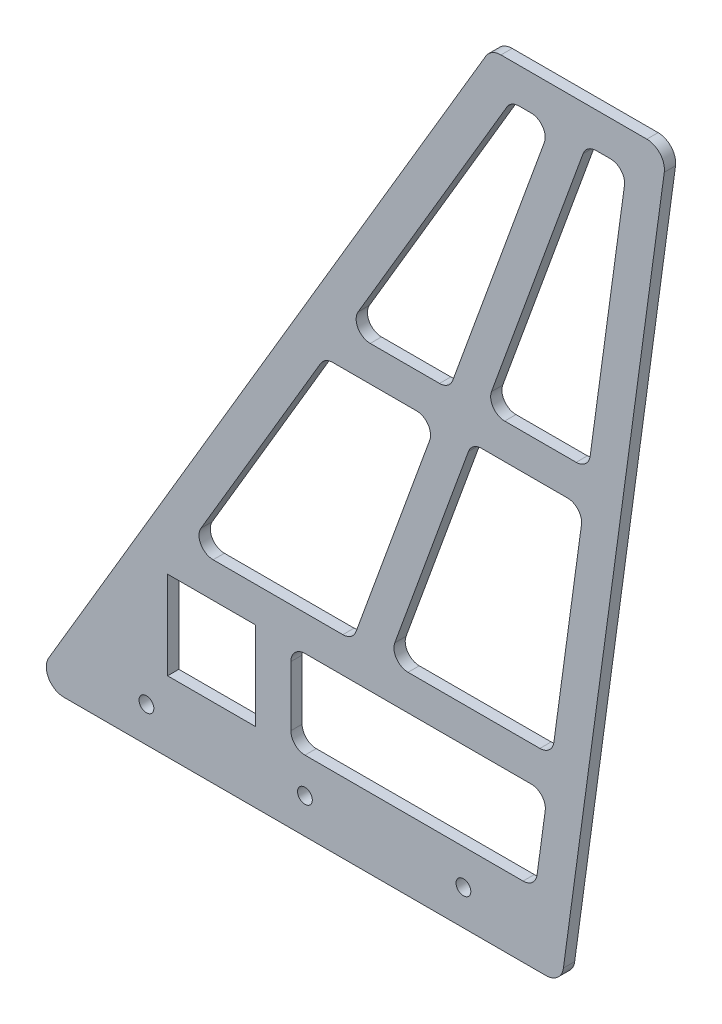
SolidWorks part; units mm, degrees
ref_plane "Спереди" through (0, 0, 0) normal (0, 0, 1) x (1, 0, 0)
ref_plane "Сверху" through (0, 0, 0) normal (0, 1, 0) x (1, 0, 0)
ref_plane "Справа" through (0, 0, 0) normal (1, 0, 0) x (0, 0, -1)
other "Configuration Table"
sketch "Эскиз1" plane through (0, 0, 0) normal (0, 0, 1) x (1, 0, 0)
  line L0 (0, 0) -> (150, 0)
  line L1 (150, 0) -> (180, 220)
  line L2 (180, 220) -> (130, 220)
  line L3 (130, 220) -> (0, 0)
  line L4 (130, 220) -> (130, 20) construction
  line L5 (135.7063, 210) -> (23.4336, 20)
  line L7 (142.6347, 20) -> (168.5438, 210)
  line L8 (168.5438, 210) -> (135.7063, 210)
  line L9 (23.4336, 20) -> (142.6347, 20)
  line L10 (135.7063, 210) -> (17.5245, 10) construction
  line L11 (17.5245, 10) -> (141.2711, 10) construction
  line L12 (130, 10) -> (130, 0) construction
  line L13 (141.2711, 10) -> (168.5438, 210) construction
  dimension "D1" = 150
  dimension "D2" = 220
  dimension "D3" = 130
  dimension "D4" = 10
  dimension "D5" = 20
extrude "Бобышка-Вытянуть1" add sketch "Эскиз1" along normal blind 3.2
fillet "Скругление1" radius 5 4 edges at (0, 0, 1.6) (150, 0, 1.6) (180, 220, 1.6) (130, 220, 1.6)
sketch "Эскиз2" plane through (0, 0, 3.2) normal (0, 0, 1) x (1, 0, 0)
  line L0 (77.1989, 0) -> (77.1989, 20) construction
  line L1 (8.7622, 0) -> (145.6355, 0) construction
  line L2 (23.4336, 20) -> (142.6347, 20) construction
  circle A0 centre (77.1989, 10) radius 2.1
  dimension "D1" = 4.2
  dimension "D2" = 10
extrude "Вырез-Вытянуть1" cut sketch "Эскиз2" against normal blind 3.2
pattern_linear "Линейный массив1" count 2 spacing 45 along (1, 0, 0) count 2 spacing 45 along (-1, 0, 0) of "Вырез-Вытянуть1"
sketch "Эскиз3" plane through (0, 0, 0) normal (0, 0, 1) x (1, 0, 0)
  line L1 (135.7063, 210) -> (23.4336, 20) construction
  line L2 (142.6347, 20) -> (168.5438, 210) construction
  line L6 (70.7063, 100) -> (107.1251, 100)
  line L7 (153.5438, 100) -> (154.9075, 110)
  line L8 (154.9075, 110) -> (120.7614, 110)
  line L9 (76.6154, 110) -> (70.7063, 100)
  line L10 (152.1251, 210) -> (83.0342, 20) construction
  line L11 (168.5438, 210) -> (135.7063, 210) construction
  line L12 (23.4336, 20) -> (142.6347, 20) construction
  line L17 (147.1251, 210) -> (110.7614, 110)
  line L18 (78.0342, 20) -> (88.0342, 20)
  line L19 (88.0342, 20) -> (117.1251, 100)
  line L20 (147.1251, 210) -> (157.1251, 210)
  line L21 (120.7614, 110) -> (157.1251, 210)
  line L22 (110.7614, 110) -> (76.6154, 110)
  line L23 (107.1251, 100) -> (78.0342, 20)
  line L24 (117.1251, 100) -> (153.5438, 100)
  dimension "D1" = 100
  dimension "D2" = 10
  dimension "D7" = 10
  dimension "D8" = 5
sketch "Эскиз4" plane through (0, 0, 0) normal (0, 0, 1) x (1, 0, 0)
  line L0 (38.2063, 45) -> (63.2063, 45)
  line L1 (135.7063, 210) -> (23.4336, 20) construction
  line L2 (142.6347, 20) -> (168.5438, 210) construction
  line L3 (146.0438, 45) -> (147.4075, 55)
  line L4 (147.4075, 55) -> (100.7614, 55)
  line L5 (44.1154, 55) -> (38.2063, 45)
  line L6 (23.4336, 20) -> (142.6347, 20) construction
  line L7 (38.2063, 45) -> (38.2063, 20)
  line L8 (152.1251, 210) -> (83.0342, 20) construction
  line L9 (63.2063, 20) -> (63.2063, 45)
  line L10 (73.2063, 45) -> (73.2063, 20)
  line L11 (38.2063, 45) -> (23.4336, 20)
  line L12 (23.4336, 20) -> (38.2063, 20)
  line L13 (73.2063, 45) -> (146.0438, 45)
  line L14 (73.2063, 20) -> (63.2063, 20)
  line L15 (168.5438, 210) -> (135.7063, 210) construction
  line L16 (23.4336, 20) -> (142.6347, 20) construction
  line L17 (157.1251, 210) -> (128.216, 130.5)
  line L18 (147.1251, 210) -> (157.1251, 210)
  line L19 (90.7614, 55) -> (114.5796, 120.5)
  line L20 (82.8199, 120.5) -> (114.5796, 120.5)
  line L21 (135.7063, 210) -> (23.4336, 20) construction
  line L22 (142.6347, 20) -> (168.5438, 210) construction
  line L23 (156.3393, 120.5) -> (157.7029, 130.5)
  line L24 (157.7029, 130.5) -> (128.216, 130.5)
  line L25 (88.729, 130.5) -> (82.8199, 120.5)
  line L26 (124.5796, 120.5) -> (100.7614, 55)
  line L27 (118.216, 130.5) -> (88.729, 130.5)
  line L28 (118.216, 130.5) -> (147.1251, 210)
  line L29 (124.5796, 120.5) -> (156.3393, 120.5)
  line L30 (90.7614, 55) -> (44.1154, 55)
  dimension "D1" = 10
  dimension "D2" = 25
  dimension "D3" = 25
  dimension "D4" = 10
  dimension "D5" = 5
  dimension "D6" = 10
  dimension "D7" = 10
  dimension "D8" = 65.5
extrude "Бобышка-Вытянуть2" add sketch "Эскиз4" along normal blind 3.2 contours L8 L18 L28 L27 L25 L20 L19 L30 L5 L0 L9 L14 L10 L13 | L18 L8 L13 L3 L4 L26 L29 L23 L24 L17 | L7 L12 L11
fillet "Скругление2" radius 4 20 edges at (147.4075, 55, 1.6) (100.7614, 55, 1.6) (124.5796, 120.5, 1.6) (156.3393, 120.5, 1.6) (114.5796, 120.5, 1.6) (44.1154, 55, 1.6) (82.8199, 120.5, 1.6) (90.7614, 55, 1.6) (168.5438, 210, 1.6) (157.1251, 210, 1.6) (128.216, 130.5, 1.6) (157.7029, 130.5, 1.6) (118.216, 130.5, 1.6) (88.729, 130.5, 1.6) (147.1251, 210, 1.6) (135.7063, 210, 1.6) (73.2063, 45, 1.6) (73.2063, 20, 1.6) (146.0438, 45, 1.6) (142.6347, 20, 1.6)
